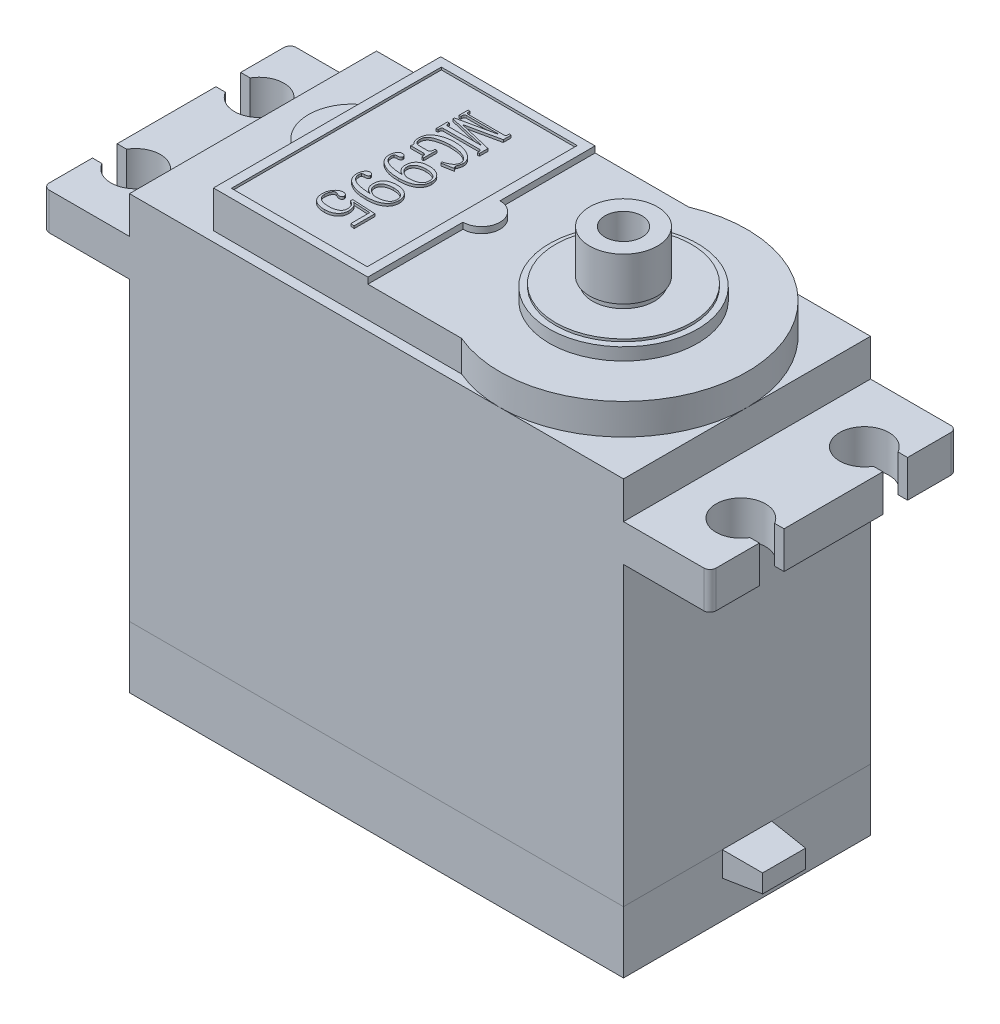
SolidWorks part; units mm, degrees
other "标注1"
sketch "草图21" plane through (27, 26.2, -0.0001) normal (0.5082, 0.7163, -0.4782) x (0.7119, -0.6619, -0.2348)
ref_plane "前视基准面" through (0, 0, 0) normal (0, 0, 1) x (1, 0, 0)
ref_plane "上视基准面" through (0, 0, 0) normal (0, 1, 0) x (1, 0, 0)
ref_plane "右视基准面" through (0, 0, 0) normal (1, 0, 0) x (0, 0, -1)
sketch "草图1" plane through (0, 0, 0) normal (0, 0, 1) x (1, 0, 0)
  line L1 (-20, 18.5) -> (20, 18.5)
  line L2 (-20, 18.5) -> (-20, -18.5)
  line L3 (-20, -18.5) -> (20, -18.5)
  line L4 (20, 18.5) -> (20, -18.5)
  line L5 (-20, 18.5) -> (20, -18.5) construction
  line L6 (-20, -18.5) -> (20, 18.5) construction
  point P0 (0, 0)
  dimension "D1" = 40
  dimension "D2" = 37
extrude "凸台-拉伸1" add sketch "草图1" along normal blind 20
chamfer "倒角1" distance 2 angle 45 4 edges at (-20, -18.5, 10) (0, -18.5, 0) (20, -18.5, 10) (0, -18.5, 20)
sketch "草图2" plane through (0, 18.5, 0) normal (0, 1, 0) x (1, 0, 0)
  line L0 (-14, -0.8) -> (-14, -19.2)
  line L3 (19.2, -0.8) -> (-13.2, -0.8) construction
  line L4 (-13.2, -19.2) -> (19.2, -19.2) construction
  line L7 (-20, -20) -> (-20, 0) construction
  line L8 (-14, 0) -> (-14, -20) construction
  line L9 (-14, -19.2) -> (19.2, -19.2)
  line L10 (19.2, -19.2) -> (19.2, -0.8)
  line L11 (19.2, -0.8) -> (-14, -0.8)
  line L12 (-13.2, -0.8) -> (-13.2, -19.2) construction
  line L13 (20, -20) -> (20, 0) construction
  line L14 (20, 0) -> (-14, 0) construction
  line L15 (-14, -20) -> (20, -20) construction
  dimension "D1" = 6
  dimension "D2" = 0.8
extrude "凸台-拉伸2" add sketch "草图2" along normal blind 3
sketch "草图3" plane through (0, 21.5, 0) normal (0, 1, 0) x (1, 0, 0)
  line L0 (19.2, -10) -> (-1.51, -10) construction
  line L1 (19.2, -19.2) -> (19.2, -0.8) construction
  line L2 (20, -20) -> (20, 0) construction
  circle A0 centre (10, -10) radius 10
  dimension "D1" = 20
  dimension "D2" = 10
extrude "凸台-拉伸3" add sketch "草图3" against normal up to surface (3 mm away) up to face at (0, 18.5, 10)
sketch "草图4" plane through (0, 21.5, 0) normal (0, 1, 0) x (1, 0, 0)
  line L0 (13.9192, -0.8) -> (19.2, -0.8)
  line L1 (19.2, -0.8) -> (19.2, -6.0808)
  line L2 (13.9192, -19.2) -> (19.2, -19.2)
  line L3 (19.2, -19.2) -> (19.2, -13.9192)
  arc A0 (13.9192, -19.2) -> (19.2, -13.9192) centre (10, -10) ccw
  arc A1 (19.2, -6.0808) -> (13.9192, -0.8) centre (10, -10) ccw
extrude "切除-拉伸1" cut sketch "草图4" against normal up to surface (3 mm away) up to face at (-4.4899, 18.5, 10)
sketch "草图5" plane through (0, 21.5, 0) normal (0, 1, 0) x (1, 0, 0)
  line L0 (-1.5, -0.8) -> (-1.5, -20)
  line L1 (6.0808, -0.8) -> (-14, -0.8) construction
  line L2 (10, -20) -> (-20, -20) construction
  line L3 (-1.5, -20) -> (20, -20)
  line L4 (20, -20) -> (20, 0)
  line L5 (20, 0) -> (-1.5, 0)
  line L6 (10, 0) -> (-20, 0) construction
  line L7 (-1.5, 0) -> (-1.5, -0.8)
  line L8 (-14, -0.8) -> (-14, -19.2) construction
  dimension "D1" = 12.5
extrude "切除-拉伸2" cut sketch "草图5" against normal blind 0.5
sketch "草图6" plane through (0, 21, 0) normal (0, 1, 0) x (1, 0, 0)
  line L0 (-1.5, -0.8) -> (-1.5, -19.2) construction
  circle A0 centre (-1.5, -10) radius 1.5
  dimension "D1" = 3
extrude "凸台-拉伸4" add sketch "草图6" along normal blind 0.5
sketch "草图7" plane through (0, 21, 0) normal (0, 1, 0) x (1, 0, 0)
  circle A0 centre (10, -10) radius 6
  dimension "D1" = 12
extrude "凸台-拉伸5" add sketch "草图7" along normal blind 1
sketch "草图8" plane through (0, 22, 0) normal (0, 1, 0) x (1, 0, 0)
  circle A0 centre (10, -10) radius 5.5
  dimension "D1" = 11
extrude "凸台-拉伸6" add sketch "草图8" along normal blind 0.2
sketch "草图9" plane through (0, 22.2, 0) normal (0, 1, 0) x (1, 0, 0)
  circle A0 centre (10, -10) radius 2.75
  dimension "D1" = 5.5
extrude "凸台-拉伸7" add sketch "草图9" along normal blind 4
sketch "草图10" plane through (0, 26.2, 0) normal (0, 1, 0) x (1, 0, 0)
  circle A0 centre (10, -10) radius 1.5
  dimension "D1" = 3
extrude "切除-拉伸3" cut sketch "草图10" against normal blind 3
sketch "草图12" plane through (0, 22.2, 0) normal (0, 1, 0) x (1, 0, 0)
  circle A0 centre (10, -10) radius 2.75
  circle A1 centre (10, -10) radius 2.5
  dimension "D1" = 5.5
  dimension "D2" = 5
extrude "切除-拉伸4" cut sketch "草图12" along normal blind 0.5
sketch "草图13" plane through (0, 18.5, 0) normal (0, 1, 0) x (1, 0, 0)
  line L0 (20, 0) -> (27, 0)
  line L1 (27, 0) -> (27, -20)
  line L2 (27, -20) -> (20, -20)
  line L3 (20, 0) -> (20, -20)
  line L4 (20, -20) -> (20.1131, -19.9478)
  line L5 (0, 0) -> (0, 12.9941) construction
  line L6 (-20, -20) -> (-20.1131, -19.9478)
  line L7 (-20, 0) -> (-20, -20)
  line L8 (-27, -20) -> (-20, -20)
  line L9 (-27, 0) -> (-27, -20)
  line L10 (-20, 0) -> (-27, 0)
  dimension "D1" = 7
extrude "凸台-拉伸8" add sketch "草图13" along normal blind 3 from offset 6 offset against normal yes
sketch "草图14" plane through (0, 15.5, 0) normal (0, 1, 0) x (1, 0, 0)
  line L0 (20, -10) -> (27, -10) construction
  line L1 (20, 0) -> (20, -20) construction
  line L2 (27, 0) -> (27, -20) construction
  line L3 (20, -5) -> (27, -5) construction
  line L4 (20, -10) -> (20, 0) construction
  line L5 (0, 0) -> (0, 4.7101) construction
  circle A0 centre (24.5, -5) radius 2
  circle A1 centre (24.5, -15) radius 2
  circle A2 centre (-24.5, -15) radius 2
  circle A3 centre (-24.5, -5) radius 2
  dimension "D1" = 4
  dimension "D2" = 4.5
extrude "切除-拉伸5" cut sketch "草图14" against normal through all
sketch "草图15" plane through (0, 15.5, 0) normal (0, 1, 0) x (1, 0, 0)
  line L0 (22.5, -5) -> (27.7382, -5) construction
  line L1 (20, -10) -> (30.0109, -10) construction
  line L2 (24.892, -4) -> (28.0369, -4)
  line L3 (24.892, -4) -> (24.892, -6)
  line L4 (24.892, -6) -> (28.0369, -6)
  line L5 (28.0369, -4) -> (28.0369, -6)
  line L6 (24.892, -4) -> (28.0369, -6) construction
  line L7 (24.892, -6) -> (28.0369, -4) construction
  line L8 (24.892, -14) -> (28.0369, -16) construction
  line L9 (24.892, -16) -> (28.0369, -14) construction
  line L10 (28.0369, -16) -> (28.0369, -14)
  line L11 (24.892, -14) -> (28.0369, -14)
  line L12 (24.892, -16) -> (24.892, -14)
  line L13 (24.892, -16) -> (28.0369, -16)
  line L14 (0, 0) -> (0, 7.6415) construction
  line L15 (-24.892, -16) -> (-28.0369, -14) construction
  line L16 (-24.892, -14) -> (-28.0369, -16) construction
  line L17 (-24.892, -6) -> (-28.0369, -4) construction
  line L18 (-24.892, -4) -> (-28.0369, -6) construction
  line L19 (-24.892, -16) -> (-28.0369, -16)
  line L20 (-24.892, -16) -> (-24.892, -14)
  line L21 (-24.892, -14) -> (-28.0369, -14)
  line L22 (-28.0369, -16) -> (-28.0369, -14)
  line L23 (-28.0369, -4) -> (-28.0369, -6)
  line L24 (-24.892, -6) -> (-28.0369, -6)
  line L25 (-24.892, -4) -> (-24.892, -6)
  line L26 (-24.892, -4) -> (-28.0369, -4)
  circle A0 centre (24.5, -5) radius 2 construction
  arc A1 (6.0808, -19.2) -> (6.0808, -0.8) centre (10, -10) ccw construction
  point P5 (26.4645, -5)
  point P20 (26.4645, -15)
  point P32 (-26.4645, -15)
  point P33 (-26.4645, -5)
  dimension "D1" = 2
extrude "切除-拉伸6" cut sketch "草图15" against normal through all
fillet "圆角1" radius 0.5 4 edges at (-27, 14, 20) (-27, 14, 0) (27, 14, 0) (27, 14, 20)
sketch "草图16" plane through (0, 21.5, 0) normal (0, 1, 0) x (1, 0, 0)
  line L0 (-14, -0.8) -> (-14, -19.2) construction
  line L1 (-14, -7.1277) -> (-14, -12.8723)
  arc A0 (-14, -7.1277) -> (-14, -12.8723) centre (-12, -10) ccw
  point P2 (-14, -10)
  dimension "D1" = 7
  dimension "D2" = 2
extrude "凸台-拉伸9" add sketch "草图16" against normal up to surface (2.8 mm away) from offset 0.2 up to face at (-4.4899, 18.5, 10) offset against normal yes
sketch "草图17" plane through (0, 0, 20) normal (0, 0, 1) x (1, 0, 0)
  line L0 (-24.6577, -11.5) -> (27.1144, -11.5)
  line L1 (18, -18.5) -> (-18, -18.5) construction
  dimension "D1" = 7
split line "分割线1"
sketch "草图18" plane through (20, 0, 0) normal (1, 0, 0) x (0, 0, -1)
  line L0 (-10, -16.5) -> (-10, 4.3504) construction
  line L1 (-20, -16.5) -> (0, -16.5) construction
  line L2 (-20, -11.5) -> (0, -11.5) construction
  line L3 (-12, -11.5) -> (-8, -11.5)
  line L4 (-12, -11.5) -> (-12, -13.5)
  line L5 (-12, -13.5) -> (-8, -13.5)
  line L6 (-8, -11.5) -> (-8, -13.5)
  line L7 (-12, -11.5) -> (-8, -13.5) construction
  line L8 (-12, -13.5) -> (-8, -11.5) construction
  point P4 (-10, -12.5)
  dimension "D1" = 2
  dimension "D2" = 4
extrude "凸台-拉伸10" add sketch "草图18" along normal blind 3 draft 5
sketch "草图19" plane through (0, 21.5, 0) normal (0, 1, 0) x (1, 0, 0)
  line L0 (-14, -10) -> (0, -10) construction
  line L1 (-2.25, -18.5) -> (-13.25, -18.5)
  line L2 (-2.25, -18.5) -> (-2.25, -1.5)
  line L3 (-2.25, -1.5) -> (-13.25, -1.5)
  line L4 (-13.25, -18.5) -> (-13.25, -1.5)
  line L5 (-2.25, -18.5) -> (-13.25, -1.5) construction
  line L6 (-2.25, -1.5) -> (-13.25, -18.5) construction
  line L7 (-14, -12.8723) -> (-14, -7.1277) construction
  line L8 (-7.75, -0.8) -> (-7.75, -19.2) construction
  line L9 (-1.5, -0.8) -> (-14, -0.8) construction
  line L10 (-14, -19.2) -> (-1.5, -19.2) construction
  arc A0 (-1.5, -11.5) -> (-1.5, -8.5) centre (-1.5, -10) ccw construction
  point P0 (-7.75, -10)
  dimension "D1" = 11
  dimension "D2" = 17
extrude "切除-拉伸7" cut sketch "草图19" against normal blind 0.2
sketch "草图20" plane through (0, 21.3, 0) normal (0, 1, 0) x (1, 0, 0)
  line L0 (-9.25, -1.5) -> (-9.25, -18.5) construction
  line L1 (-2.25, -1.5) -> (-13.25, -1.5) construction
  line L2 (-13.25, -18.5) -> (-2.25, -18.5) construction
  line L3 (-13.25, -1.5) -> (-13.25, -18.5) construction
  text T0 "MG995" font "幼圆" height 3.5
  dimension "D1" = 4
extrude "凸台-拉伸11" add sketch "草图20" along normal blind 0.2
